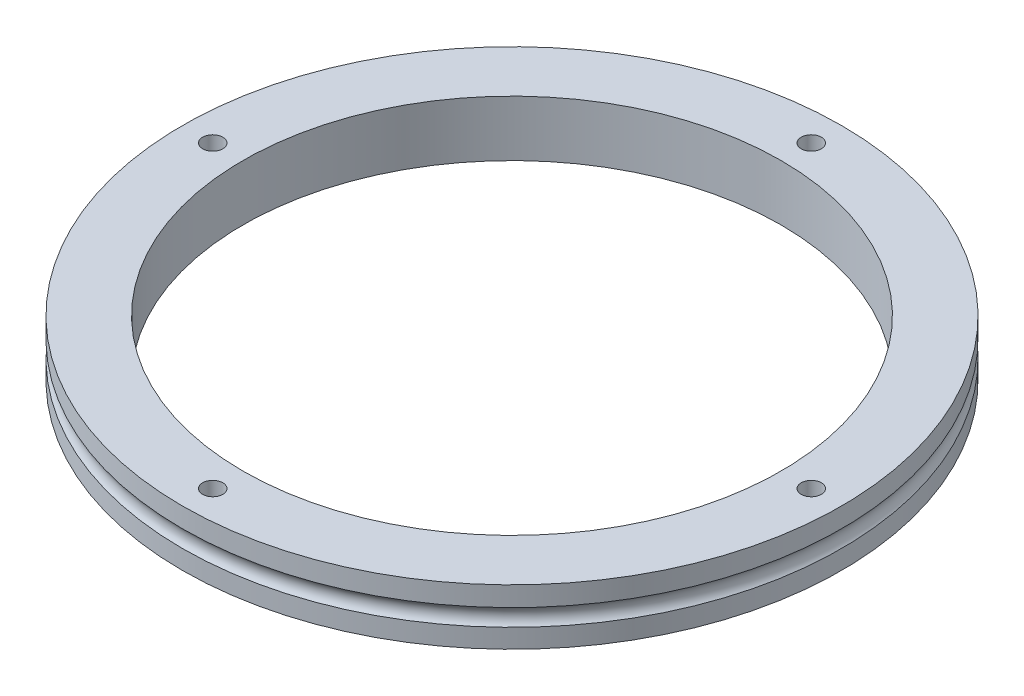
SolidWorks part; units mm, degrees
ref_plane "前视基准面" through (0, 0, 0) normal (0, 0, 1) x (1, 0, 0)
ref_plane "上视基准面" through (0, 0, 0) normal (0, 1, 0) x (1, 0, 0)
ref_plane "右视基准面" through (0, 0, 0) normal (1, 0, 0) x (0, 0, -1)
other "Configuration Table"
sketch "草图5" plane through (0, 0, 0) normal (0, 0, 1) x (1, 0, 0)
  line L0 (-46.7522, 16.7881) -> (2.2478, 16.7881)
  line L1 (-46.7522, 16.7881) -> (-46.7522, 13.8566)
  line L2 (2.2478, 16.7881) -> (2.2478, 8.4881)
  line L3 (-46.7522, 8.4881) -> (2.2478, 8.4881)
  line L6 (-46.7522, 11.3195) -> (-46.7522, 8.4881)
  arc A0 (-46.2522, 12.5881) -> (-46.7522, 13.8566) centre (-48.1114, 12.5881) ccw
  arc A1 (-46.2522, 12.5881) -> (-46.7522, 11.3195) centre (-48.1114, 12.5881) cw
  dimension "D1" = 8.3
  dimension "D2" = 49
revolve "旋转2" add sketch "草图5" angle 360 about L2
sketch "草图7" plane through (0, 0, 0) normal (0, 1, 0) x (1, 0, 0)
  circle A0 centre (2.2478, 0) radius 40
  circle A1 centre (2.2478, 0) radius 49 construction
  dimension "D1" = 9
extrude "切除-拉伸1" cut sketch "草图7" along normal through all
ref_plane "基准面1" through (0, 12.6381, 0) normal (0, 1, 0) x (1, 0, 0)
sketch "草图8" plane through (0, 16.7881, 0) normal (0, 1, 0) x (1, 0, 0)
  circle A2 centre (2.2478, 44.5) radius 1.5
  circle A3 centre (46.7478, 0) radius 1.5
  circle A4 centre (2.2478, -44.5) radius 1.5
  circle A5 centre (-42.2522, 0) radius 1.5
extrude "切除-拉伸2" cut sketch "草图8" against normal blind 10
